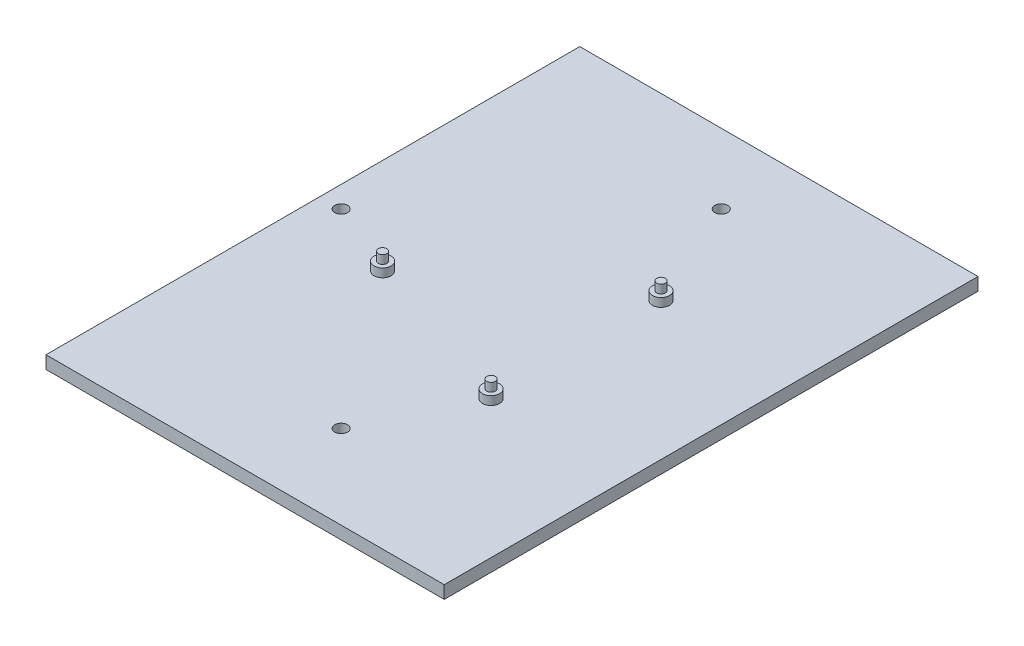
SolidWorks part; units mm, degrees
ref_plane "Front Plane" through (0, 0, 0) normal (0, 0, 1) x (1, 0, 0)
ref_plane "Top Plane" through (0, 0, 0) normal (0, 1, 0) x (1, 0, 0)
ref_plane "Right Plane" through (0, 0, 0) normal (1, 0, 0) x (0, 0, -1)
sketch "Sketch1" plane through (0, 0, 0) normal (0, 1, 0) x (1, 0, 0)
  line L1 (-53.4821, 119.3245) -> (39.7679, 119.3245)
  line L2 (-53.4821, 119.3245) -> (-53.4821, -5.6755)
  line L3 (-53.4821, -5.6755) -> (39.7679, -5.6755)
  line L4 (39.7679, 119.3245) -> (39.7679, -5.6755)
  dimension "D1" = 93.25
  dimension "D2" = 125
extrude "Boss-Extrude1" add sketch "Sketch1" along normal blind 3
sketch "Sketch2" plane through (0, 3, 0) normal (0, 1, 0) x (1, 0, 0)
  point P0 (-3.9821, 102.9479)
  point P1 (-3.9821, 13.9479)
  point P3 (-48.4821, 58.4479)
sketch "Sketch3" plane through (0, 3, 0) normal (0, 1, 0) x (1, 0, 0)
  circle A0 centre (-3.9821, 102.9479) radius 1.5
extrude "Cut-Extrude1" cut sketch "Sketch3" against normal blind 3
pattern_sketch "Sketch-Pattern1" of "Cut-Extrude1" driven by "Sketch2"
sketch "Sketch4" plane through (0, 3, 0) normal (0, 1, 0) x (1, 0, 0)
  circle A0 centre (-31.0821, 50.7479) radius 2
  circle A1 centre (-31.0821, 50.7479) radius 1
  point P0 (-31.0821, 50.7479)
  point P1 (7.5179, 38.5479)
  point P3 (7.5179, 78.3479)
  dimension "D1" = 4
  dimension "D2" = 2
extrude "Boss-Extrude2" add sketch "Sketch4" along normal blind 2
sketch "Sketch6" plane through (0, 3, 0) normal (0, 1, 0) x (1, 0, 0)
  circle A0 centre (-31.0821, 50.7479) radius 1
  dimension "D1" = 2
extrude "Boss-Extrude3" add sketch "Sketch6" along normal blind 4
sketch "Sketch7" plane through (0, 3, 0) normal (0, 1, 0) x (1, 0, 0)
  point P0 (7.5179, 77.3479)
  point P1 (7.5179, 37.5479)
  point P3 (-31.0821, 50.7479)
  point P5 (0, 0)
pattern_sketch "Sketch-Pattern2" of "Boss-Extrude3", "Boss-Extrude2" driven by "Sketch7"
